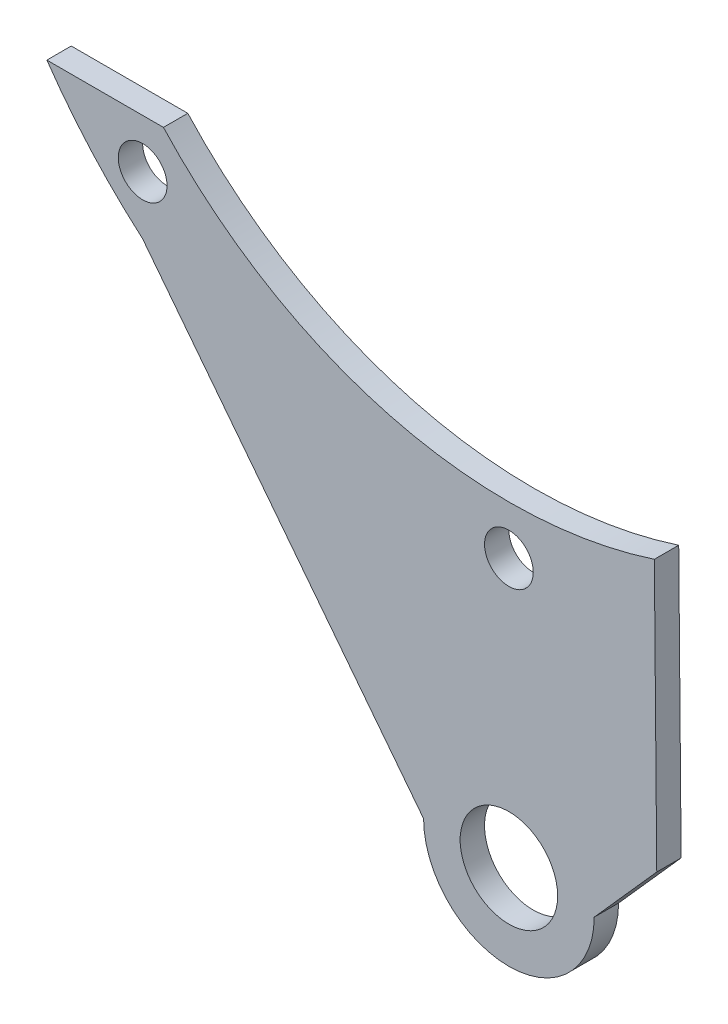
SolidWorks part; units mm, degrees
other "标注1"
sketch "草图2" plane through (-37.6526, -60.6295, 0) normal (-0.1807, -0.2096, -0.9609) x (-0.9832, 0.0643, 0.1709)
ref_plane "前视基准面" through (0, 0, 0) normal (0, 0, 1) x (1, 0, 0)
ref_plane "上视基准面" through (0, 0, 0) normal (0, 1, 0) x (1, 0, 0)
ref_plane "右视基准面" through (0, 0, 0) normal (1, 0, 0) x (0, 0, -1)
sketch "草图1" plane through (0, 0, 0) normal (0, 0, 1) x (1, 0, 0)
  line L0 (-29.793, -29.1816) -> (-29.793, -25.1816) construction
  line L1 (-28.0878, -25.1816) -> (-37.6526, -25.1816)
  line L2 (28.6059, -25.1816) -> (38.1707, -25.1816) construction
  line L3 (0.259, -41.6295) -> (0.259, -63.6295) construction
  line L10 (-6.741, -63.6295) -> (-29.793, -33.9559)
  line L12 (12.1939, -35.7329) -> (12.392, -57.8561)
  line L13 (7.259, -63.6295) -> (12.392, -57.8561)
  circle A0 centre (0.259, 0.8705) radius 42.5 construction
  circle A1 centre (0.259, -41.6295) radius 2
  circle A2 centre (-29.793, -29.1816) radius 2
  circle A3 centre (30.3111, -29.1816) radius 2 construction
  circle A4 centre (0.259, 0.8705) radius 38.5 construction
  circle A5 centre (0.259, 0.8705) radius 46 construction
  circle A6 centre (0.259, -63.6295) radius 4
  arc A7 (-37.6526, -25.1816) -> (-29.793, -33.9559) centre (0.259, 0.8705) ccw
  arc A8 (30.7909, -33.536) -> (38.1707, -25.1816) centre (0.259, 0.8705) ccw construction
  arc A9 (-28.0878, -25.1816) -> (28.6059, -25.1816) centre (0.259, 0.8705) ccw construction
  arc A12 (12.1939, -35.7329) -> (-28.0878, -25.1816) centre (0.259, 0.8705) cw
  circle A13 centre (0.259, -63.6295) radius 7 construction
  arc A14 (-6.741, -63.6295) -> (7.259, -63.6295) centre (0.259, -63.6295) ccw
extrude "凸台-拉伸1" add sketch "草图1" along normal blind 2
ref_point "点1"
